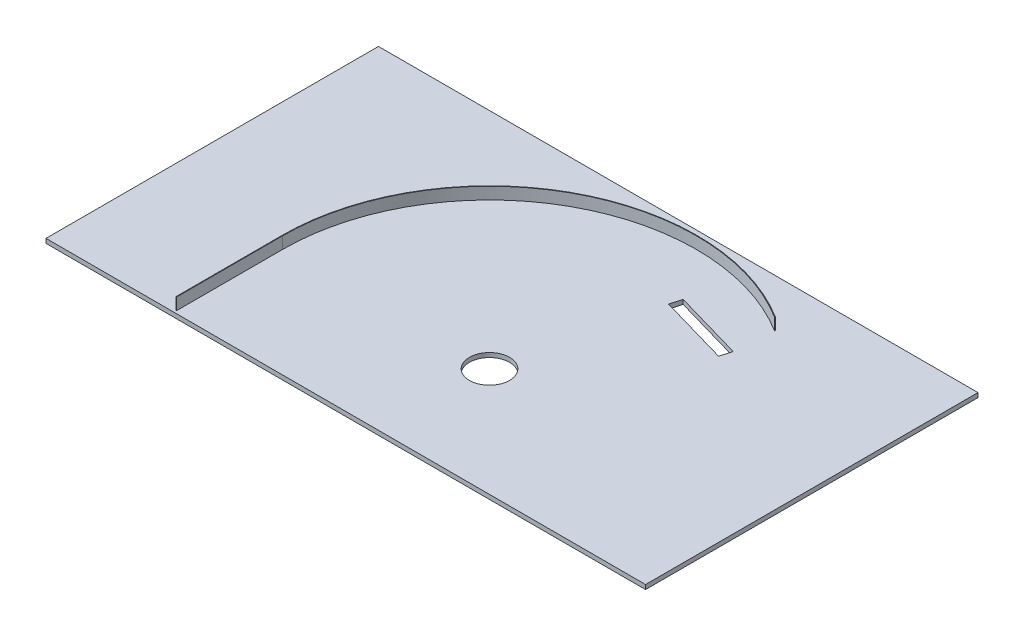
SolidWorks part; units mm, degrees
material "Particle Board"
ref_plane "Front Plane" through (0, 0, 0) normal (0, 0, 1) x (1, 0, 0)
ref_plane "Top Plane" through (0, 0, 0) normal (0, 1, 0) x (1, 0, 0)
ref_plane "Right Plane" through (0, 0, 0) normal (1, 0, 0) x (0, 0, -1)
sketch "Sketch3" plane through (0, 0, 0) normal (0, 1, 0) x (1, 0, 0)
  line L1 (0, 0) -> (-839.8654, 0) construction
  line L2 (0, 0) -> (-451.1992, 260.5) construction
  line L5 (-524, 0) -> (-525.5875, 0)
  line L6 (277.6777, 444.3772) -> (277.6777, 446.248)
  circle A0 centre (0, 0) radius 254 construction
  arc A3 (277.6777, 444.3772) -> (-524, 0) centre (0, 0) ccw
  arc A4 (277.6777, 446.248) -> (-525.5875, 0) centre (0, 0) ccw
  arc A5 (278.5189, 445.7235) -> (-525.5875, 0) centre (0, 0) ccw construction
  dimension "D1" = 524
  dimension "D2" = 1.5875
  dimension "D4" = 122
  dimension "D5" = 508
  dimension "D3" = 30
extrude "Boss-Extrude1" add sketch "Sketch3" along normal blind 30
sketch "Sketch4" plane through (0, 0, 0) normal (0, 1, 0) x (1, 0, 0)
  line L5 (-848, 566.7) -> (670.6777, 566.7)
  line L6 (-848, 566.7) -> (-848, -275.4)
  line L7 (-848, -275.4) -> (670.6777, -275.4)
  line L8 (670.6777, 566.7) -> (670.6777, -275.4)
  dimension "D1" = 275.4
  dimension "D2" = 848
  dimension "D3" = 566.7
  dimension "D4" = 393
extrude "Boss-Extrude2" add sketch "Sketch4" against normal blind 11.1125
hole_wizard "Ø20.0mm Dowel Hole1" positions "Sketch6" profile "Sketch7" hole size "Ø20.0" standard "ANSI Metric" end condition through all
sketch "Sketch6" plane through (0, 0, 0) normal (0, 1, 0) x (1, 0, 0)
  point P0 (0, 0)
sketch "Sketch7" plane through (0, 0, 0) normal (1, 0, 0) x (0, 0, 1)
  line L0 (0, 0) -> (0, 11.1125)
  line L1 (0, 11.1125) -> (50.8, 11.1125)
  line L2 (50.8, 11.1125) -> (50.8, 0)
  line L5 (50.8, 0) -> (0, 0)
  line L11 (0, -6.35) -> (0, 107.95) construction
  dimension "Thru Hole Dia." = 101.6
  dimension "Thru Hole Depth" = 11.1125
ref_plane "Plane1" through (0, 0, 269.05) normal (0, 0, 1) x (1, 0, 0)
sketch "Sketch8" plane through (0, 0, 0) normal (0, 0, 1) x (1, 0, 0)
  line L1 (-525.5875, 30) -> (-524, 30)
  line L2 (-525.5875, 30) -> (-525.5875, 0)
  line L3 (-525.5875, 0) -> (-524, 0)
  line L4 (-524, 30) -> (-524, 0)
extrude "Boss-Extrude3" add sketch "Sketch8" along normal up to surface (269.05 mm away) up to plane "Plane1"
sketch "Sketch9" plane through (0, 0, 0) normal (0, 1, 0) x (1, 0, 0)
  line L0 (270.6691, 346.7379) -> (92.8357, 397.7308)
  line L1 (92.8357, 397.7308) -> (84.5666, 368.8929)
  line L2 (84.5666, 368.8929) -> (262.4, 317.9)
  line L3 (262.4, 317.9) -> (270.6691, 346.7379)
  line L6 (0, 0) -> (670.6777, 0) construction
  line L7 (670.6777, -275.4) -> (670.6777, 566.7) construction
  dimension "D1" = 185
  dimension "D2" = 30
  dimension "D3" = 16
  dimension "D4" = 262.4
  dimension "D5" = 317.9
extrude "Cut-Extrude1" cut sketch "Sketch9" against normal through all
